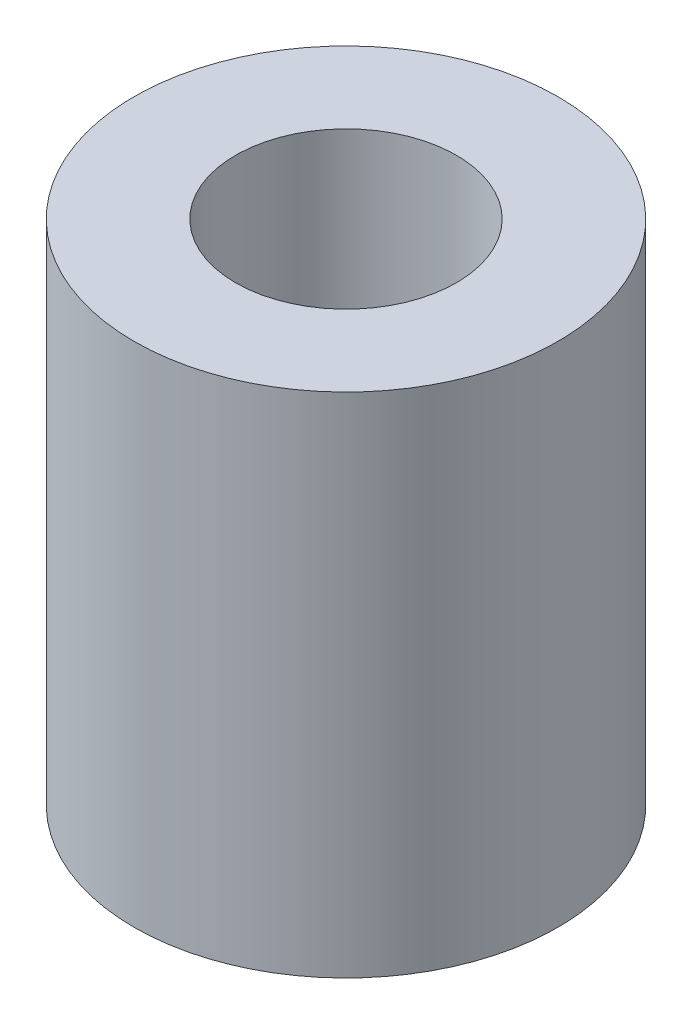
SolidWorks part; units mm, degrees
ref_plane "Front Plane" through (0, 0, 0) normal (0, 0, 1) x (1, 0, 0)
ref_plane "Top Plane" through (0, 0, 0) normal (0, 1, 0) x (1, 0, 0)
ref_plane "Right Plane" through (0, 0, 0) normal (1, 0, 0) x (0, 0, -1)
sketch "Sketch1" plane through (0, 0, 0) normal (0, 1, 0) x (1, 0, 0)
  circle A0 centre (-0.3344, 0.1068) radius 9.017
  circle A1 centre (-0.3344, 0.1068) radius 4.699
  dimension "D1" = 18.034
  dimension "D2" = 9.398
extrude "Boss-Extrude1" add sketch "Sketch1" along normal blind 21.59
